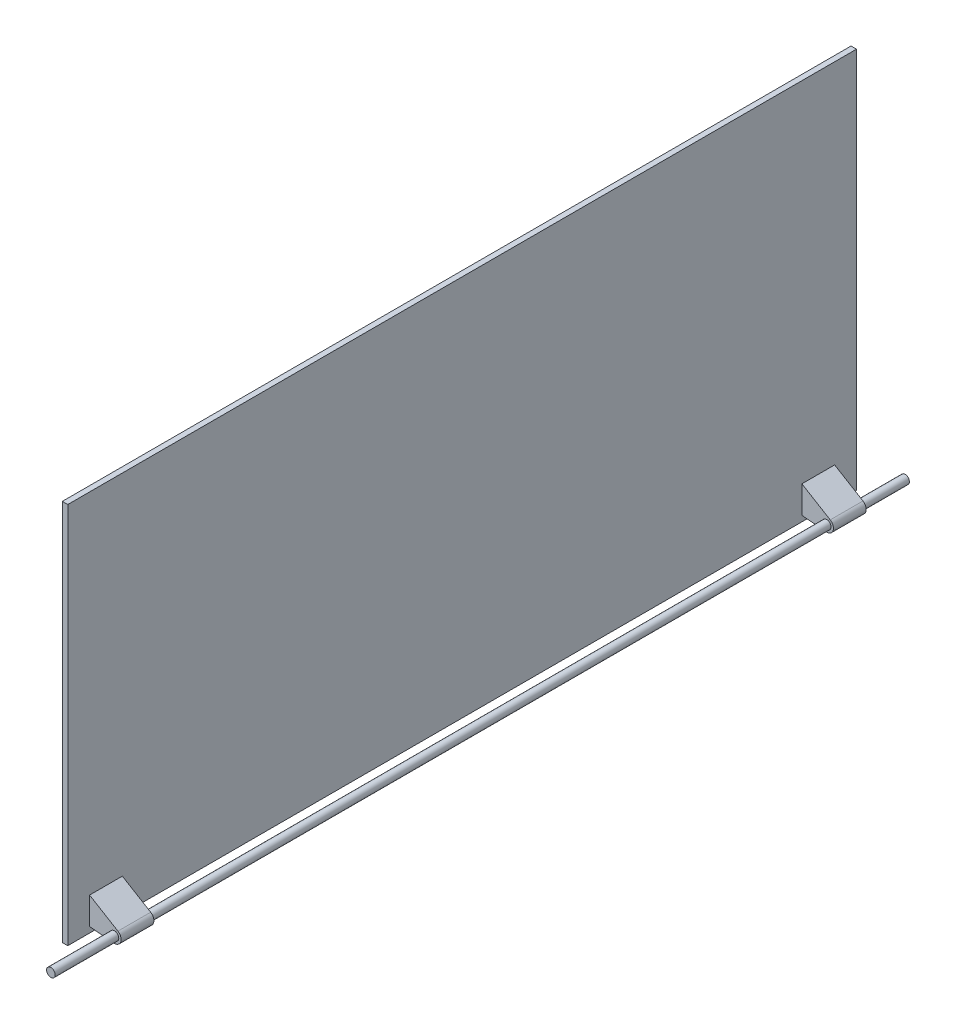
SolidWorks part; units mm, degrees
ref_plane "Front Plane" through (0, 0, 0) normal (0, 0, 1) x (1, 0, 0)
ref_plane "Top Plane" through (0, 0, 0) normal (0, 1, 0) x (1, 0, 0)
ref_plane "Right Plane" through (0, 0, 0) normal (1, 0, 0) x (0, 0, -1)
sketch "Sketch1" plane through (0, 0, 0) normal (1, 0, 0) x (0, 0, -1)
  line L1 (-367.03, 177.8) -> (367.03, 177.8)
  line L2 (-367.03, 177.8) -> (-367.03, -177.8)
  line L3 (-367.03, -177.8) -> (367.03, -177.8)
  line L4 (367.03, 177.8) -> (367.03, -177.8)
  line L5 (-367.03, 177.8) -> (367.03, -177.8) construction
  line L6 (-367.03, -177.8) -> (367.03, 177.8) construction
  point P0 (0, 0)
  dimension "D1" = 355.6
  dimension "D2" = 734.06
extrude "Boss-Extrude1" add sketch "Sketch1" along normal blind 5.08
ref_plane "Plane1" through (0, 0, 316.23) normal (0, 0, 1) x (1, 0, 0)
sketch "Sketch5" plane through (5.08, 0, 0) normal (1, 0, 0) x (0, 0, -1)
  line L0 (-316.23, 79.3747) -> (-316.23, -79.3747) construction
  line L1 (-357.3269, -147.1331) -> (-316.23, -147.1331)
  line L2 (-357.3269, -147.1331) -> (-357.3269, -172.5331)
  line L3 (-357.3269, -172.5331) -> (-316.23, -172.5331)
  line L4 (-316.23, -147.1331) -> (-316.23, -172.5331)
  line L5 (-357.3269, -147.1331) -> (-316.23, -172.5331) construction
  line L6 (-357.3269, -172.5331) -> (-316.23, -147.1331) construction
  point P0 (-336.7785, -159.8331)
  dimension "D1" = 25.4
sketch "Sketch6" plane through (0, 0, 316.23) normal (0, 0, 1) x (1, 0, 0)
  line L0 (5.08, -147.1331) -> (5.08, -172.5331)
  line L1 (5.08, -172.5331) -> (27.6916, -174.5222)
  line L3 (31.4392, -163.0287) -> (5.08, -147.1331)
  arc A0 (27.6916, -174.5222) -> (31.4392, -163.0287) centre (28.2353, -168.3417) ccw
  circle A1 centre (28.2353, -168.3417) radius 4.0005
  dimension "D1" = 8.001
  dimension "D2" = 25.4
extrude "Boss-Extrude2" add sketch "Sketch6" along normal blind 30.48 separate body
mirror "Mirror5" about plane through (0, 0, 0) normal (0, 0, 1) of bodies 102
sketch "Sketch7" plane through (0, 0, 346.71) normal (0, 0, 1) x (1, 0, 0)
  circle A0 centre (28.2353, -168.3417) radius 4.0005 construction
  circle A1 centre (28.2353, -168.3417) radius 4.0005
extrude "Boss-Extrude3" add sketch "Sketch7" along normal blind 59.182 and the other way blind 735.838
